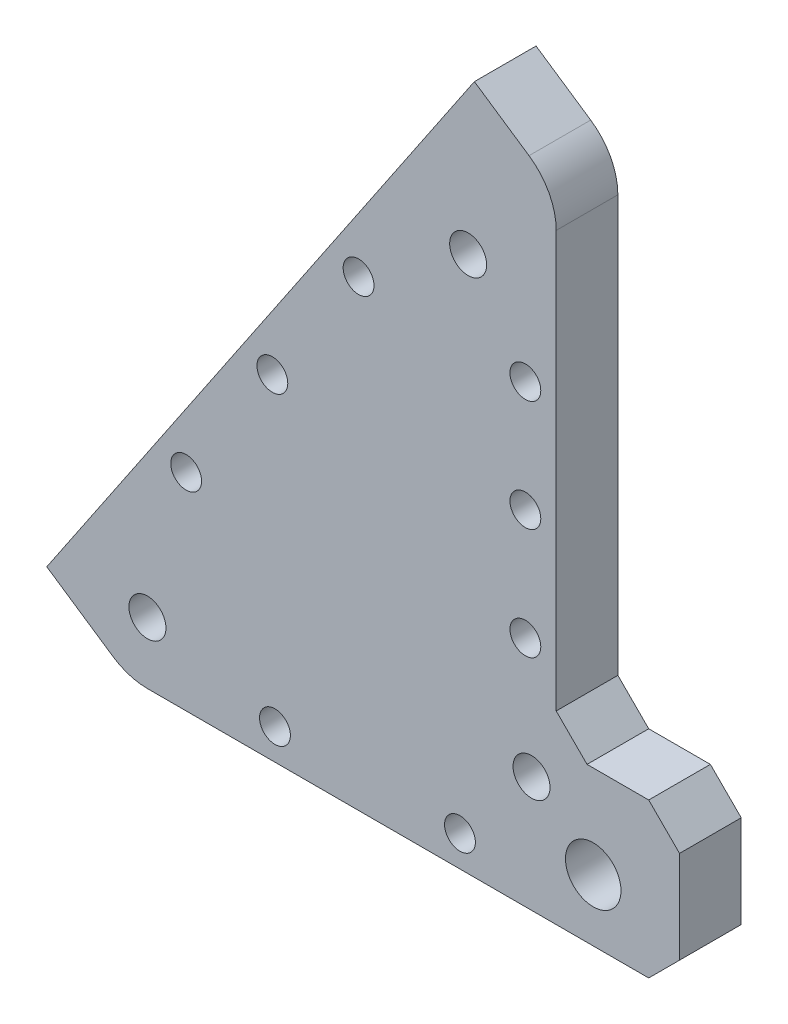
SolidWorks part; units mm, degrees
ref_plane "Спереди" through (0, 0, 0) normal (0, 0, 1) x (1, 0, 0)
ref_plane "Сверху" through (0, 0, 0) normal (0, 1, 0) x (1, 0, 0)
ref_plane "Справа" through (0, 0, 0) normal (1, 0, 0) x (0, 0, -1)
other "Configuration Table"
sketch "Эскиз2" plane through (0, 0, 0) normal (0, 0, 1) x (1, 0, 0)
  line L11 (-28.7037, -22.3645) -> (-0.7441, 19.0874) construction
  line L12 (-14.3023, -50.8739) -> (15.6977, -50.8739) construction
  line L13 (26.3023, 17.8739) -> (26.3023, -18.1261) construction
  line L14 (-34.9804, -55.8739) -> (46.3023, -55.8739)
  line L15 (46.3023, -55.8739) -> (51.3023, -50.8739)
  line L16 (51.3023, -50.8739) -> (51.3023, -35.8739)
  line L17 (51.3023, -35.8739) -> (46.3023, -30.8739)
  line L18 (46.3023, -30.8739) -> (36.3023, -30.8739)
  line L19 (36.3023, -30.8739) -> (31.3023, -25.8739)
  line L20 (31.3023, -25.8739) -> (31.3023, 41.6097)
  line L21 (26.8942, 49.9001) -> (18.0377, 55.8739)
  line L22 (18.0377, 55.8739) -> (-51.3023, -46.9268)
  line L23 (-51.3023, -46.9268) -> (-40.5723, -54.1642)
  circle A2 centre (27.3023, -37.1261) radius 3
  circle A3 centre (17.0259, 31.1261) radius 3
  arc A4 (31.3023, 41.6097) -> (26.8942, 49.9001) centre (21.3023, 41.6097) ccw
  arc A5 (-40.5723, -54.1642) -> (-34.9804, -55.8739) centre (-34.9804, -45.8739) ccw
  circle A6 centre (-34.9804, -45.8739) radius 3
  circle A7 centre (-28.7037, -22.3645) radius 2.5
  circle A8 centre (-14.7239, -1.6386) radius 2.5
  circle A9 centre (-0.7441, 19.0874) radius 2.5
  circle A10 centre (-14.3023, -50.8739) radius 2.5
  circle A11 centre (15.6977, -50.8739) radius 2.5
  circle A12 centre (26.3023, 17.8739) radius 2.5
  circle A13 centre (26.3023, -0.1261) radius 2.5
  circle A14 centre (26.3023, -18.1261) radius 2.5
  circle A15 centre (37.3023, -45.8739) radius 4.5
  dimension "D1" = 6
  dimension "D5" = 5
  dimension "D16" = 9
  dimension "D17" = 14
  dimension "D2" = 5
  dimension "D3" = 50
  dimension "D4" = 33
  dimension "D6" = 5
  dimension "D7" = 30
  dimension "D8" = 37
  dimension "D9" = 5
  dimension "D10" = 5
  dimension "D11" = 36
  dimension "D12" = 38
  dimension "D13" = 13
  dimension "D14" = 87
  dimension "D15" = 93
  dimension "D18" = 10
extrude "Бобышка-Вытянуть1" add sketch "Эскиз2" along normal blind 10
